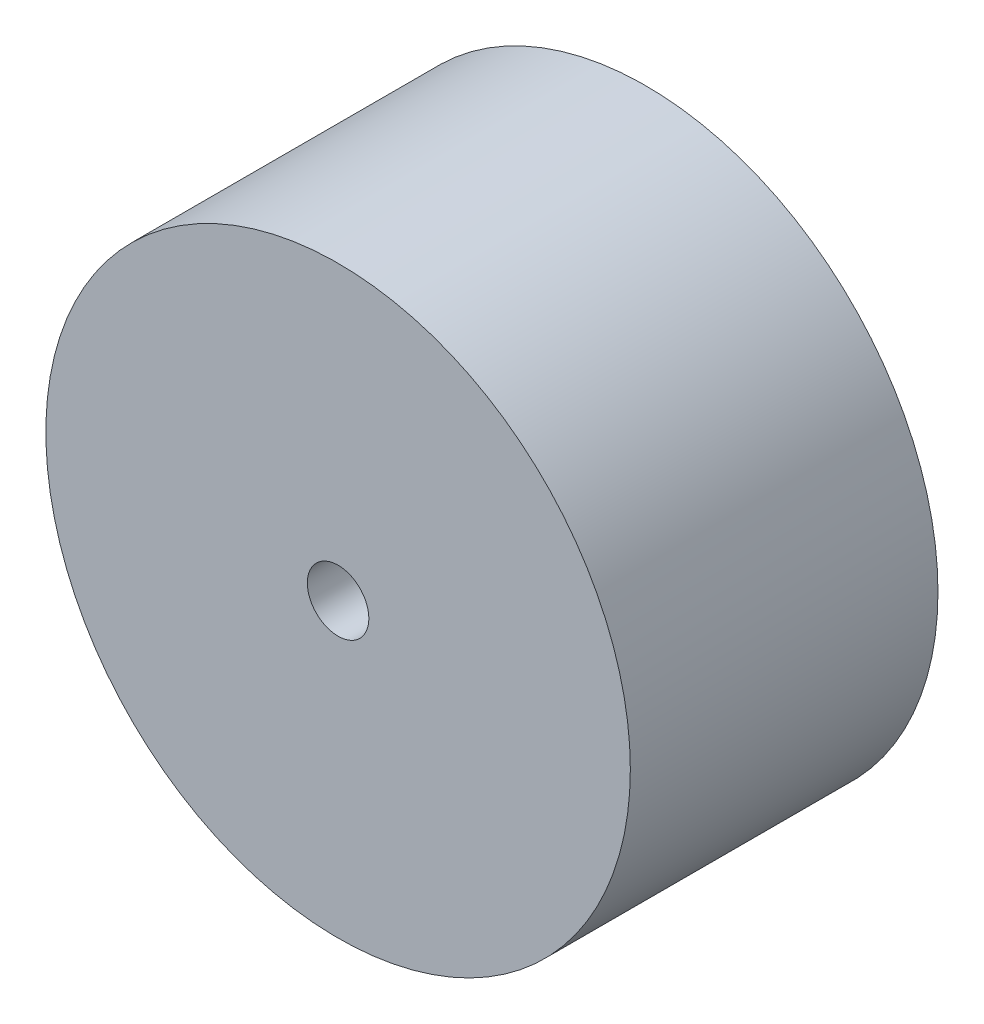
SolidWorks part; units mm, degrees
ref_plane "正面" through (0, 0, 0) normal (0, 0, 1) x (1, 0, 0)
ref_plane "平面" through (0, 0, 0) normal (0, 1, 0) x (1, 0, 0)
ref_plane "右側面" through (0, 0, 0) normal (1, 0, 0) x (0, 0, -1)
sketch "ｽｹｯﾁ1" plane through (0, 0, 0) normal (0, 0, 1) x (1, 0, 0)
  circle A0 centre (-12.6941, 1.2144) radius 28.5
  dimension "D1" = 57
extrude "ﾎﾞｽ - 押し出し1" add sketch "ｽｹｯﾁ1" along normal blind 30
sketch "ｽｹｯﾁ2" plane through (0, 0, 30) normal (0, 0, 1) x (1, 0, 0)
  circle A0 centre (-12.6941, 1.2144) radius 3
  circle A1 centre (-12.6941, 1.2144) radius 28.5 construction
extrude "ｶｯﾄ - 押し出し1" cut sketch "ｽｹｯﾁ2" against normal blind 40
